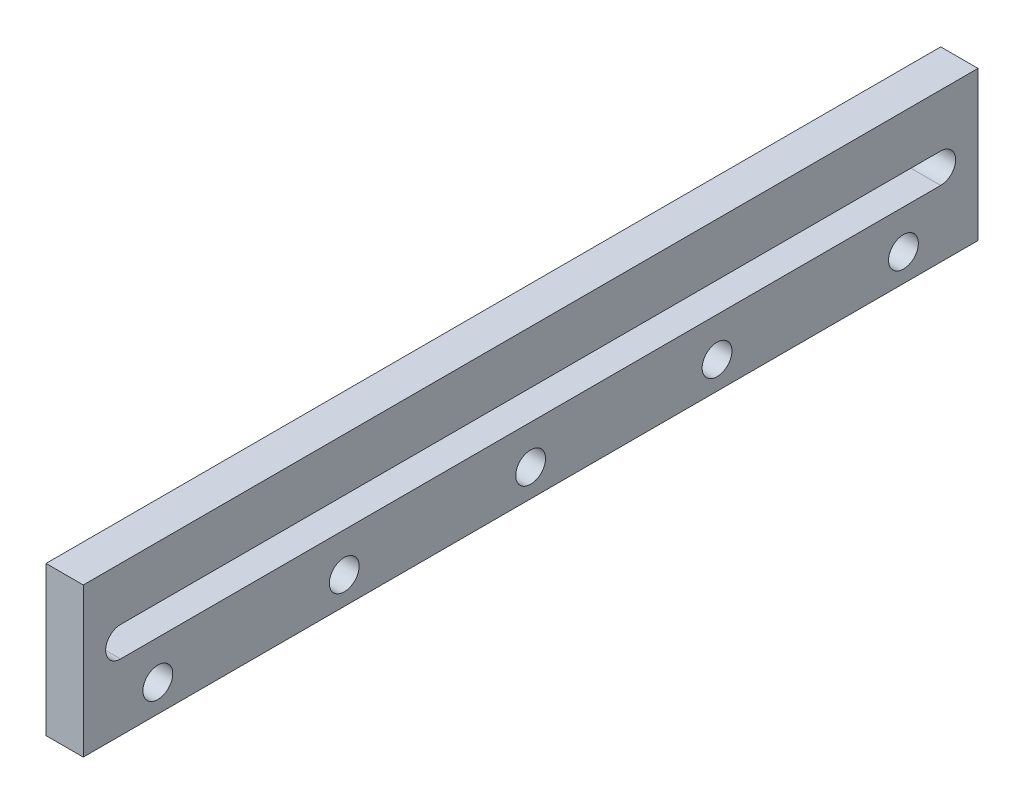
SolidWorks part; units mm, degrees
ref_plane "前视基准面" through (0, 0, 0) normal (0, 0, 1) x (1, 0, 0)
ref_plane "上视基准面" through (0, 0, 0) normal (0, 1, 0) x (1, 0, 0)
ref_plane "右视基准面" through (0, 0, 0) normal (1, 0, 0) x (0, 0, -1)
sketch "草图2" plane through (0, 0, 0) normal (1, 0, 0) x (0, 0, -1)
  line L0 (-60, -6.3057) -> (60, -6.3057)
  line L1 (-60, 10) -> (60, 10)
  line L2 (-60, 10) -> (-60, -10)
  line L3 (-60, -10) -> (60, -10)
  line L4 (60, 10) -> (60, -10)
  line L5 (-60, 10) -> (60, -10) construction
  line L6 (-60, -10) -> (60, 10) construction
  line L7 (-50, -6.3057) -> (50, -6.3057)
  line L8 (-50, -6.3057) -> (-25, -6.3057)
  line L9 (-25, -6.3057) -> (0, -6.3057)
  line L10 (0, -6.3057) -> (25, -6.3057)
  line L11 (-55, -1.0926) -> (55, -1.0926)
  line L12 (55, 2.9074) -> (-55, 2.9074)
  line L13 (-55, 2.9074) -> (-55, -1.0926)
  line L14 (55, 2.9074) -> (55, -1.0926)
  circle A0 centre (-50, -6.3057) radius 2
  circle A2 centre (0, -6.3057) radius 2
  circle A3 centre (25, -6.3057) radius 2
  circle A4 centre (50, -6.3057) radius 2
  circle A5 centre (-25, -6.3057) radius 2
  arc A6 (-55, 2.9074) -> (-55, -1.0926) centre (-55, 0.9074) ccw
  arc A7 (55, -1.0926) -> (55, 2.9074) centre (55, 0.9074) ccw
  point P0 (0, 0)
  dimension "D8" = 110
  dimension "D1" = 120
  dimension "D2" = 20
  dimension "D3" = 100
  dimension "D4" = 10
  dimension "D5" = 25
  dimension "D6" = 25
  dimension "D7" = 25
  dimension "D9" = 5
  dimension "D10" = 5
extrude "凸台-拉伸1" add sketch "草图2" along normal blind 5 contours A5 L9 A2 L10 A3 L0 A4 L4 L1 L2 A0 L8 A7 L11 A6 L12 | A5 L8 A0 L0 L2 L3 L4 A4 A3 L10 A2 L9
